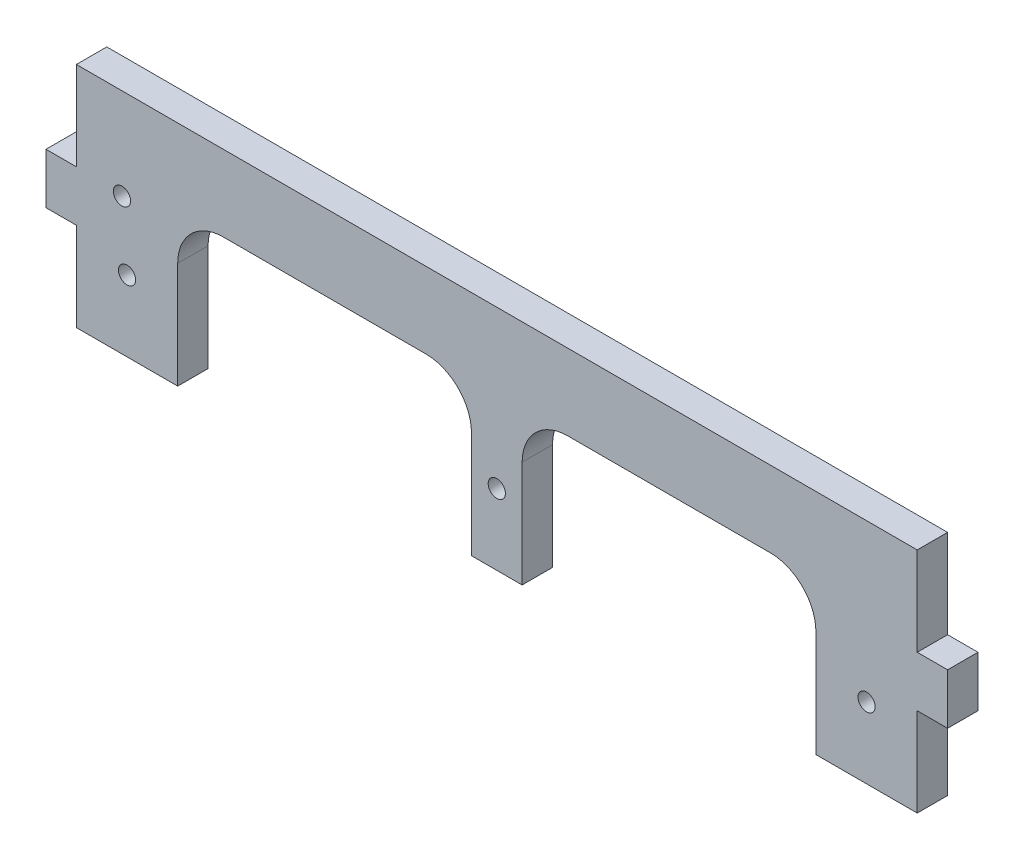
SolidWorks part; units mm, degrees
ref_plane "Front Plane" through (0, 0, 0) normal (0, 0, 1) x (1, 0, 0)
ref_plane "Top Plane" through (0, 0, 0) normal (0, 1, 0) x (1, 0, 0)
ref_plane "Right Plane" through (0, 0, 0) normal (1, 0, 0) x (0, 0, -1)
sketch "Sketch1" plane through (0, 0, 0) normal (0, 0, 1) x (1, 0, 0)
  line L0 (0, 0) -> (0, 17.5)
  line L1 (0, 45) -> (166, 45)
  line L2 (166, 45) -> (166, 27.5)
  line L3 (166, 0) -> (146, 0)
  line L4 (146, 0) -> (146, 30)
  line L5 (146, 30) -> (88, 30)
  line L6 (88, 30) -> (88, 0)
  line L7 (88, 0) -> (78, 0)
  line L8 (78, 0) -> (78, 30)
  line L9 (78, 30) -> (20, 30)
  line L10 (20, 30) -> (20, 0)
  line L11 (20, 0) -> (0, 0)
  line L12 (0, 27.5) -> (-6, 27.5)
  line L13 (-6, 27.5) -> (-6, 17.5)
  line L14 (-6, 17.5) -> (0, 17.5)
  line L15 (0, 27.5) -> (0, 45)
  line L16 (83, 45) -> (83, 0) construction
  line L17 (83, 22.5) -> (0, 22.5) construction
  line L18 (-6, 22.5) -> (20, 22.5) construction
  line L19 (172, 17.5) -> (166, 17.5)
  line L20 (172, 27.5) -> (172, 17.5)
  line L21 (166, 27.5) -> (172, 27.5)
  line L22 (166, 17.5) -> (166, 0)
  dimension "D1" = 30
  dimension "D2" = 10
  dimension "D3" = 58
  dimension "D4" = 20
  dimension "D5" = 15
  dimension "D6" = 20
  dimension "D7" = 10
  dimension "D8" = 6
extrude "Boss-Extrude1" add sketch "Sketch1" along normal blind 6
fillet "Fillet1" radius 9 4 edges at (146, 30, 3) (88, 30, 3) (78, 30, 3) (20, 30, 3)
fillet "Fillet2" [suppressed] radius 9
sketch "Sketch2" plane through (0, 0, 6) normal (0, 0, 1) x (1, 0, 0)
  line L0 (83, 45) -> (83, 0) construction
  line L1 (166, 45) -> (0, 45) construction
  line L2 (78, 0) -> (88, 0) construction
  line L3 (10, 0) -> (10, 45) construction
  line L4 (0, 0) -> (20, 0) construction
  line L5 (156, 0) -> (156, 45) construction
  line L6 (146, 0) -> (166, 0) construction
  line L7 (10, 14) -> (162.8081, 14) construction
  circle A0 centre (10, 14) radius 1.7
  circle A1 centre (83, 14) radius 1.7
  circle A2 centre (156, 14) radius 1.7
  dimension "D1" = 3.4
  dimension "D5" = 3.4
  dimension "D6" = 3.4
  dimension "D4" = 14
extrude "Cut-Extrude1" cut sketch "Sketch2" against normal through all
sketch "Sketch3" plane through (0, 0, 6) normal (0, 0, 1) x (1, 0, 0)
  circle A0 centre (9, 27) radius 1.7
  dimension "D1" = 3.4
extrude "Cut-Extrude2" cut sketch "Sketch3" against normal through all
